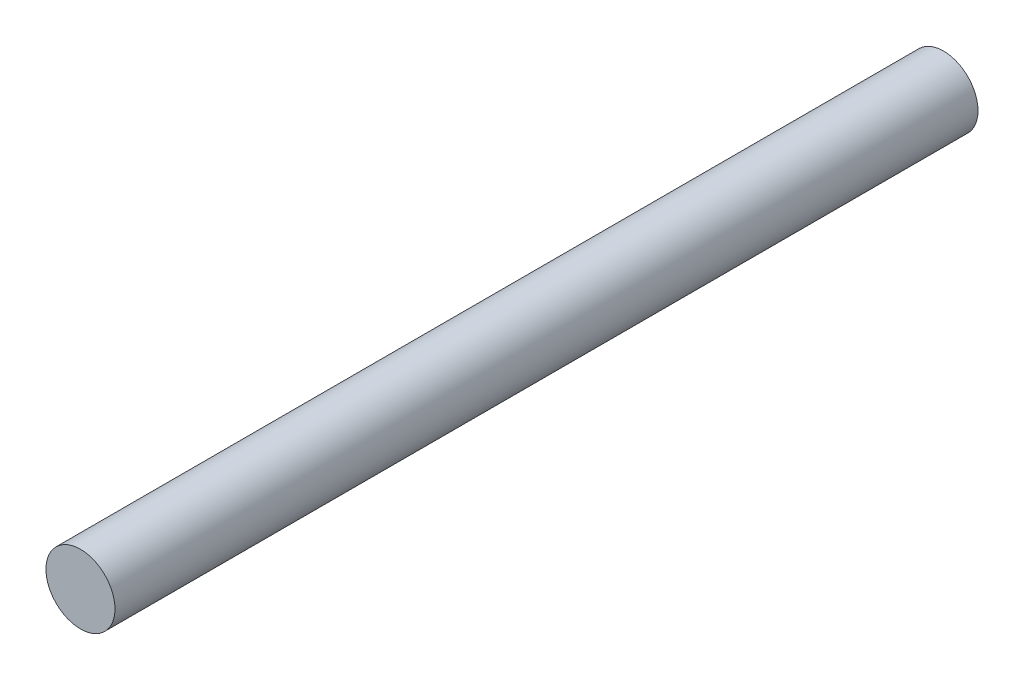
SolidWorks part; units mm, degrees
ref_plane "Front" through (0, 0, 0) normal (0, 0, 1) x (1, 0, 0)
ref_plane "Top" through (0, 0, 0) normal (0, 1, 0) x (1, 0, 0)
ref_plane "Right" through (0, 0, 0) normal (1, 0, 0) x (0, 0, -1)
sketch "Skizze1" plane through (0, 0, 0) normal (0, 0, 1) x (1, 0, 0)
  circle A0 centre (0, 0) radius 6
  dimension "D1" = 12
extrude "Aufsatz-Linear austragen1" add sketch "Skizze1" along normal blind 150
